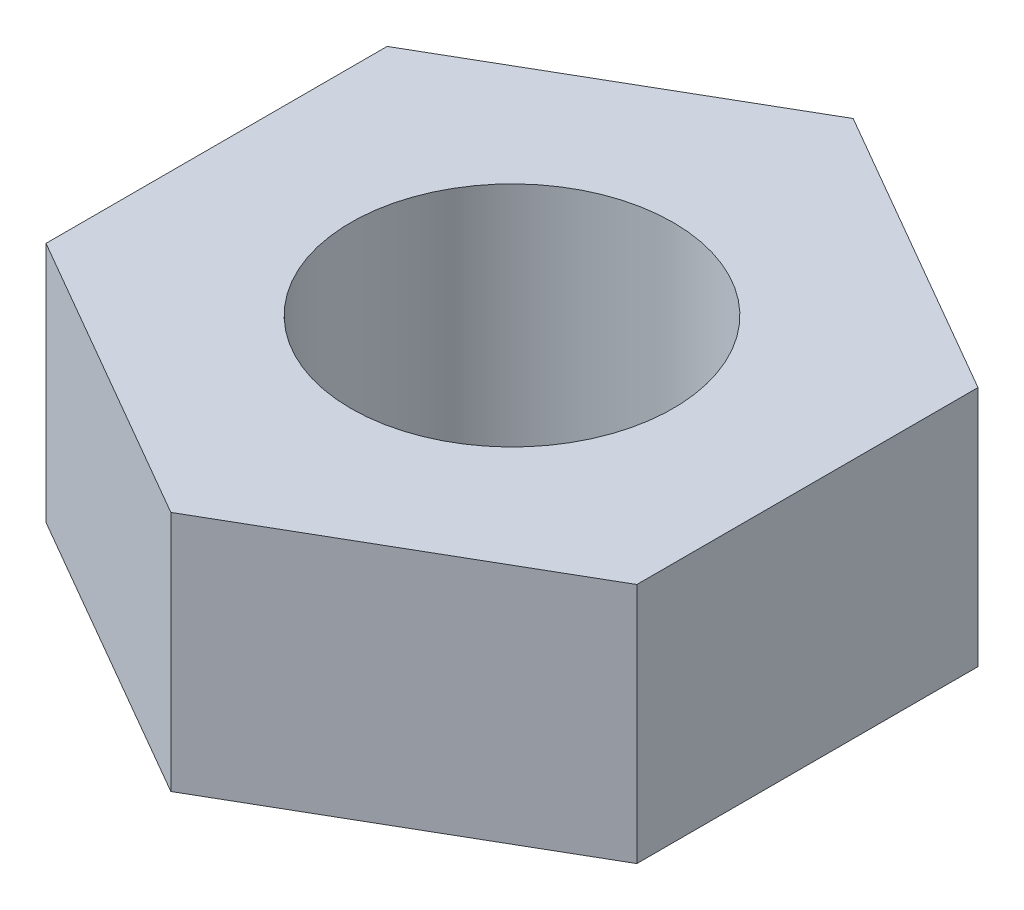
SolidWorks part; units mm, degrees
material "AISI 304"
ref_plane "Front" through (0, 0, 0) normal (0, 0, 1) x (1, 0, 0)
ref_plane "Top" through (0, 0, 0) normal (0, 1, 0) x (1, 0, 0)
ref_plane "Right" through (0, 0, 0) normal (1, 0, 0) x (0, 0, -1)
sketch "Sketch1" plane through (0, 0, 0) normal (0, 1, 0) x (1, 0, 0)
  line L1 (0, 3.1754) -> (-2.75, 1.5877)
  line L2 (-2.75, 1.5877) -> (-2.75, -1.5877)
  line L3 (-2.75, -1.5877) -> (0, -3.1754)
  line L4 (0, -3.1754) -> (2.75, -1.5877)
  line L5 (2.75, -1.5877) -> (2.75, 1.5877)
  line L6 (2.75, 1.5877) -> (0, 3.1754)
  circle A0 centre (0, 0) radius 1.5
  circle A1 centre (0, 0) radius 2.75 construction
  dimension "D1" = 3
  dimension "D2" = 5.5
extrude "Boss-Extrude1" add sketch "Sketch1" along normal blind 2.25
